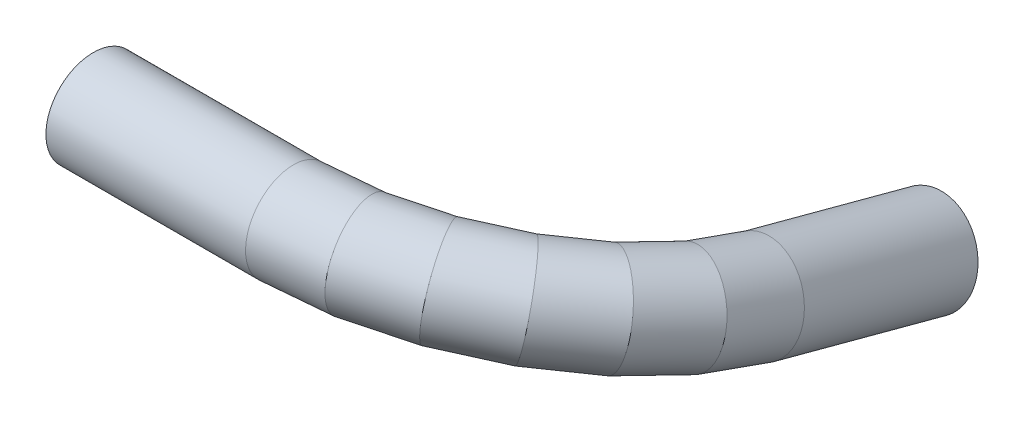
SolidWorks part; units mm, degrees
ref_plane "Front Plane" through (0, 0, 0) normal (0, 0, 1) x (1, 0, 0)
ref_plane "Top Plane" through (0, 0, 0) normal (0, 1, 0) x (1, 0, 0)
ref_plane "Right Plane" through (0, 0, 0) normal (1, 0, 0) x (0, 0, -1)
sketch3d "Path"
  line L0 (-2198.888, -22.4008, -83.6009) -> (-2179.088, -22.4008, -83.6009)
  line L1 (-2179.088, -22.4008, -83.6009) -> (-2172.8763, -22.6124, -84.3908)
  line L2 (-2172.8763, -22.6124, -84.3908) -> (-2167.088, -23.233, -86.7067)
  line L3 (-2167.088, -23.233, -86.7067) -> (-2162.1174, -24.2201, -90.3908)
  line L4 (-2162.1174, -24.2201, -90.3908) -> (-2158.3034, -25.5066, -95.192)
  line L5 (-2158.3034, -25.5066, -95.192) -> (-2155.9057, -27.0048, -100.7831)
  line L6 (-2155.9057, -27.0048, -100.7831) -> (-2155.088, -28.6124, -106.7831)
  line L7 (-2155.088, -28.6124, -106.7831) -> (-2155.088, -33.2194, -123.9766)
ref_plane "Start Plane" through (-2198.888, 0, 0) normal (1, 0, 0) x (0, 0, -1)
sketch "Profile" plane through (-2198.888, 0, 0) normal (1, 0, 0) x (0, 0, -1)
  circle A0 centre (83.6009, -22.4008) radius 4.7625
  circle A1 centre (83.6009, -22.4008) radius 3.8735
sweep "Tube" add profiles "Profile" path "Path"
